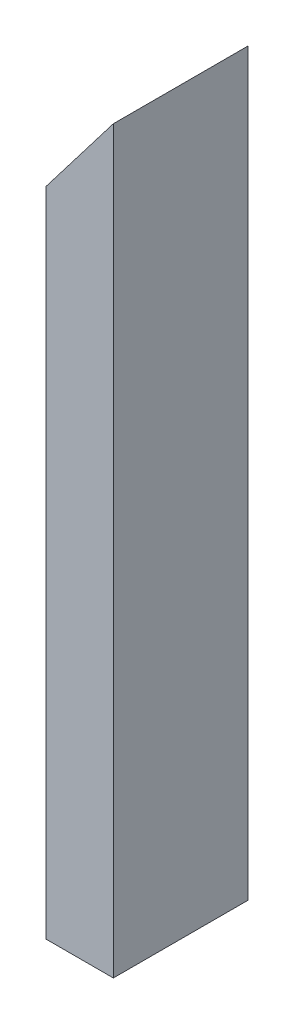
SolidWorks part; units mm, degrees
material "Brass"
ref_plane "Front Plane" through (0, 0, 0) normal (0, 0, 1) x (1, 0, 0)
ref_plane "Top Plane" through (0, 0, 0) normal (0, 1, 0) x (1, 0, 0)
ref_plane "Right Plane" through (0, 0, 0) normal (1, 0, 0) x (0, 0, -1)
sketch "Sketch1" plane through (0, 0, 0) normal (0, 0, 1) x (1, 0, 0)
  line L0 (-81.049, -45.6084) -> (-39785.8735, 30343.9772) construction
  line L1 (-1075.7055, -71.0084) -> (48924.2945, -71.0084) construction
  line L2 (0, 38.1) -> (0, 38.1001) construction
  line L3 (-692.523, -844.5158) -> (29697.0626, 38860.3087) construction
  line L4 (-81.049, -45.6084) -> (-81.049, -71.0084) construction
  line L5 (0, 60.2844) -> (-39704.8245, 30449.8699) construction
  line L6 (0, 60.2844) -> (0, -71.0084) construction
  line L7 (-6.35, 51.9879) -> (-6.35, -71.0084) construction
  line L8 (6.35, 68.5808) -> (6.35, -71.0084) construction
  line L9 (-6.35, 51.9879) -> (6.35, 68.5808)
  line L10 (6.35, 68.5808) -> (6.35, -71.0084)
  line L11 (6.35, -71.0084) -> (-6.35, -71.0084)
  line L12 (-6.35, -71.0084) -> (-6.35, 51.9879)
  dimension "D1" = 133.35
  dimension "D2" = 25.4
  dimension "D3" = 37.43
  dimension "D4" = 12.7
  dimension "D5" = 6.35
  dimension "hyp" = 20.8953
extrude "Extrude1" add sketch "Sketch1" along normal blind 25.4
hole_wizard "#10-24 Tapped Hole1" positions "Sketch2" profile "Sketch3" tap size "#10-24" standard "Ansi Inch"
sketch "Sketch2" plane through (-37.1202, 11.7858, 18.0613) normal (-0.7941, 0.6078, 0) x (0.6078, 0.7941, 0)
  point P0 (59.4462, 5.3613)
sketch "Sketch3" plane through (-0.9893, 58.9918, 12.7) normal (0, 0, 1) x (-0.6078, -0.7941, 0)
  line L0 (0, 0) -> (0, 7.7448)
  line L1 (0, 7.7448) -> (1.8986, 6.604)
  line L2 (1.8986, 6.604) -> (1.8986, 3.302)
  line L3 (1.8986, 3.302) -> (2.413, 3.302)
  line L4 (2.413, 3.302) -> (2.413, 0)
  line L5 (2.413, 0) -> (0, 0)
  line L10 (0, 7.7448) -> (-1.8987, 6.604) construction
  line L11 (0, -6.35) -> (0, 107.95) construction
  dimension "Tap Drill Dia." = 3.7973
  dimension "Tap Drill Depth" = 6.604
  dimension "Thread Major Dia." = 4.826
  dimension "Drill Angle" = 118
  dimension "Thread Depth Difference" = 3.302
hole_wizard "1/4-20 Tapped Hole2" positions "Sketch4" profile "Sketch5" tap size "1/4-20" standard "Ansi Inch"
sketch "Sketch4" plane through (-43.496, -71.0084, 18.0613) normal (0, -1, 0) x (-1, 0, 0)
  line L1 (22.1178, 5.3613) -> (22.1178, 15.989) construction
  point P0 (-43.4929, 5.3613)
sketch "Sketch5" plane through (-0.0031, -71.0084, 12.7) normal (1, 0, 0) x (0, 0, -1)
  line L0 (0, 0) -> (0, 18.0438)
  line L1 (0, 18.0438) -> (2.5527, 16.51)
  line L2 (2.5527, 16.51) -> (2.5527, 12.7)
  line L3 (2.5527, 12.7) -> (3.175, 12.7)
  line L4 (3.175, 12.7) -> (3.175, 0)
  line L5 (3.175, 0) -> (0, 0)
  line L10 (0, 18.0438) -> (-2.5527, 16.51) construction
  line L11 (0, -6.35) -> (0, 107.95) construction
  dimension "Tap Drill Dia." = 5.1054
  dimension "Tap Drill Depth" = 16.51
  dimension "Thread Major Dia." = 6.35
  dimension "Drill Angle" = 118
  dimension "Thread Depth Difference" = 3.81
